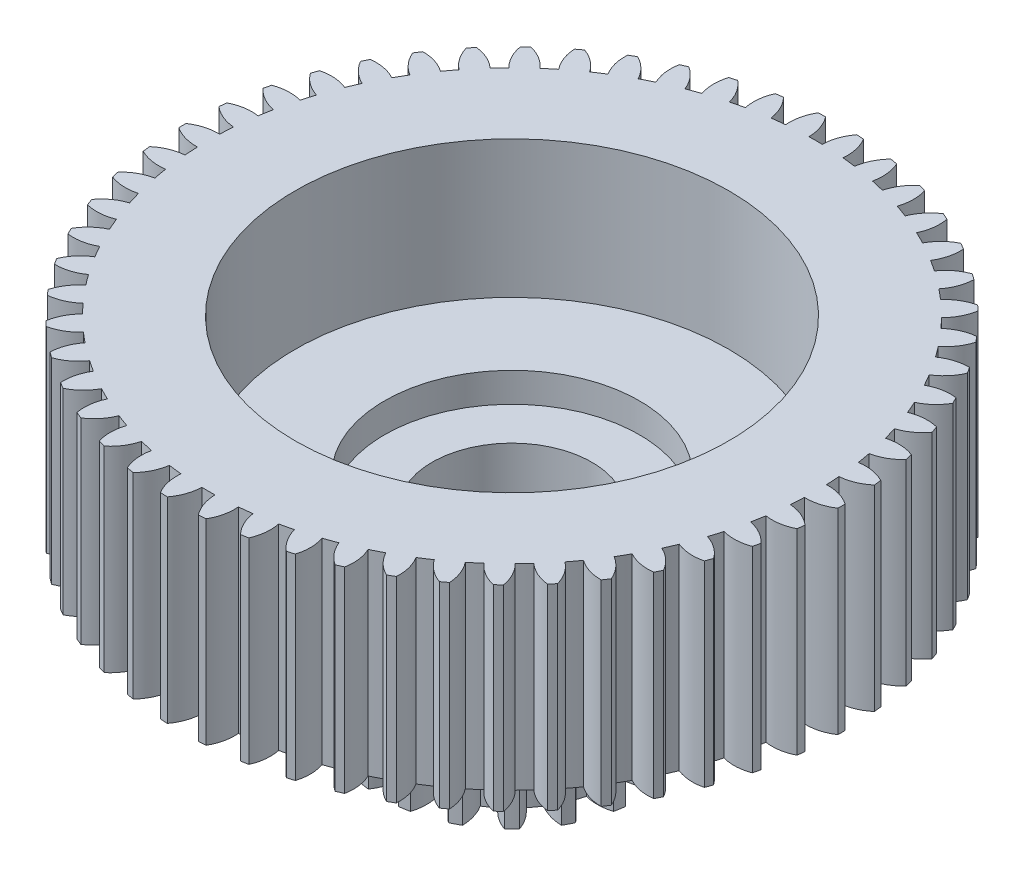
SolidWorks part; units mm, degrees
ref_plane "Ebene vorne" through (0, 0, 0) normal (0, 0, 1) x (1, 0, 0)
ref_plane "Ebene oben" through (0, 0, 0) normal (0, 1, 0) x (1, 0, 0)
ref_plane "Ebene rechts" through (0, 0, 0) normal (1, 0, 0) x (0, 0, -1)
sketch "Skizze1" plane through (0, 0, 0) normal (0, 1, 0) x (1, 0, 0)
  circle A0 centre (0, 0) radius 6.6
  circle A1 centre (0, 0) radius 4.075
  dimension "D1" = 13.2
  dimension "D2" = 8.15
extrude "Aufsatz-Linear austragen1" add sketch "Skizze1" along normal blind 8
sketch "Skizze2" plane through (0, 8, 0) normal (0, 1, 0) x (1, 0, 0)
  circle A0 centre (0, 0) radius 4.075
  circle A1 centre (0, 0) radius 16.8
  dimension "D1" = 8.15
  dimension "D2" = 33.6
extrude "Aufsatz-Linear austragen2" add sketch "Skizze2" along normal blind 10
sketch "Skizze3" plane through (0, 18, 0) normal (0, 1, 0) x (1, 0, 0)
  circle A0 centre (0, 0) radius 11.05
  dimension "D1" = 22.1
extrude "Schnitt-Linear austragen1" cut sketch "Skizze3" against normal blind 7
sketch "Skizze5" plane through (0, 0, 0) normal (0, -1, 0) x (1, 0, 0)
  line L0 (0, 0) -> (0, 6.6) construction
  line L1 (0, 0) -> (-0.3228, 5.2701) construction
  line L2 (0, 0) -> (1.0325, 6.5187) construction
  line L3 (-0.4708, 5.9815) -> (0.4708, 5.9815) construction
  line L4 (0.4708, 5.9815) -> (1.4007, 5.8342) construction
  line L5 (0, 4.6881) -> (-0.683, 6.5646) construction
  circle A0 centre (0, 0) radius 6.6
  circle A1 centre (0, 0) radius 6 construction
  circle A2 centre (0, 0) radius 5.28
  arc A3 (-5.1712, 4.1011) -> (-0.3228, 5.2701) centre (-2.8506, 5.1153) cw
  arc A4 (5.1712, 4.1011) -> (0.3228, 5.2701) centre (2.8506, 5.1153) ccw
  dimension "D2" = 13.2
  dimension "D3" = 12
  dimension "D4" = 10.56
  dimension "D1" = 20
  dimension "D5" = 9
extrude "Schnitt-Linear austragen2" cut sketch "Skizze5" against normal up to surface (8 mm away) contours A4 A0 A3 A2
pattern_circular "Kreismuster1" count 20 over 360 about axis through (0, 0, 0) along (0, 1, 0) of "Schnitt-Linear austragen2"
sketch "Skizze6" plane through (0, 18, 0) normal (0, 1, 0) x (1, 0, 0)
  line L0 (0, 0) -> (0, 16.8) construction
  line L1 (0, 0) -> (-0.3367, 15.4763) construction
  line L2 (0, 0) -> (0.9768, 16.7716) construction
  line L3 (-0.4712, 16.1931) -> (0.4712, 16.1931) construction
  line L4 (0.4712, 16.1931) -> (1.4119, 16.1384) construction
  line L5 (0, 14.8986) -> (-0.6869, 16.786) construction
  circle A0 centre (0, 0) radius 16.8
  circle A1 centre (0, 0) radius 16.2 construction
  circle A2 centre (0, 0) radius 15.48
  arc A3 (-0.792, 16.7813) -> (-0.3367, 15.4763) centre (-2.5744, 15.4277) cw
  arc A4 (0.792, 16.7813) -> (0.3367, 15.4763) centre (2.5744, 15.4277) ccw
  dimension "D1" = 33.6
  dimension "D2" = 32.4
  dimension "D3" = 30.96
  dimension "D4" = 3.333
  dimension "D5" = 20
extrude "Schnitt-Linear austragen3" cut sketch "Skizze6" along a picked direction on the side against the normal blind 10 contours A4 A0 A3 A2
pattern_circular "Kreismuster2" count 54 over 360 about axis through (0, 0, 0) along (0, 1, 0) of "Schnitt-Linear austragen3"
sketch "Skizze7" plane through (0, 11, 0) normal (0, 1, 0) x (1, 0, 0)
  circle A0 centre (0, 0) radius 6.5
  dimension "D1" = 13
extrude "Schnitt-Linear austragen4" cut sketch "Skizze7" against normal blind 1.5
equation "\"Tooth2\"= 20"
equation "\"Module\"= 0.6"
equation "\"D1@Skizze1\"=(\"Tooth2\"+2)*\"Module\""
equation "\"D4@Skizze5\"=(\"Module\"*\"Tooth2\"- (\"Module\"*if(\"Module\" => 1.25,2.25,2.4)))"
equation "\"D3@Skizze5\"=\"Tooth2\"*\"Module\""
equation "\"D2@Skizze5\"=(\"Tooth2\"+2)*\"Module\""
equation "\"D5@Skizze5\"=180/\"Tooth2\""
equation "\"D1@Kreismuster1\"=\"Tooth2\""
equation "\"Tooth1\"= 54"
equation "\"D3@Skizze6\"=(\"Module\"*\"Tooth1\"- (\"Module\"*if(\"Module\" => 1.25,2.25,2.4)))"
equation "\"D1@Skizze6\"=(\"Tooth1\"+2)*\"Module\""
equation "\"D2@Skizze6\"=\"Tooth1\"*\"Module\""
equation "\"D4@Skizze6\"=180/\"Tooth1\""
equation "\"D1@Kreismuster2\"=\"Tooth1\""
